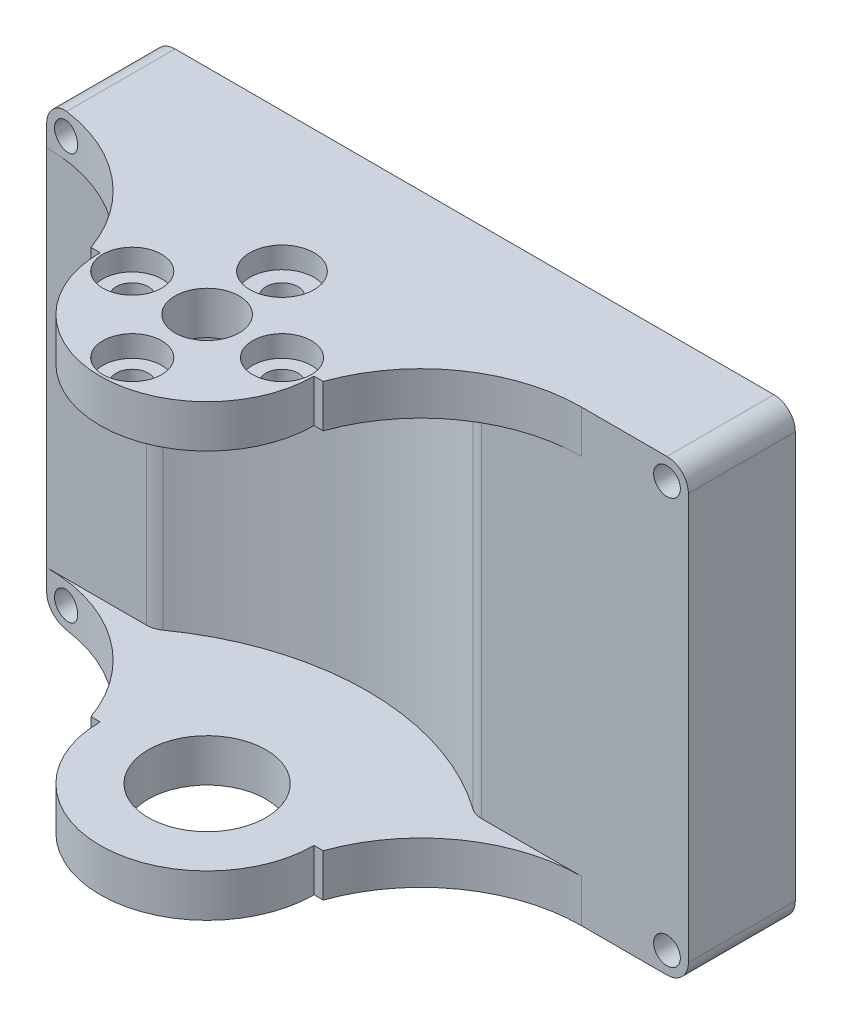
SolidWorks part; units mm, degrees
ref_plane "前视基准面" through (0, 0, 0) normal (0, 0, 1) x (1, 0, 0)
ref_plane "上视基准面" through (0, 0, 0) normal (0, 1, 0) x (1, 0, 0)
ref_plane "右视基准面" through (0, 0, 0) normal (1, 0, 0) x (0, 0, -1)
sketch "草图7" plane through (0, 0, 0) normal (0, 0, 1) x (1, 0, 0)
  line L1 (0, 0) -> (60, 0)
  line L2 (0, 0) -> (0, 42)
  line L3 (0, 42) -> (60, 42)
  line L4 (60, 0) -> (60, 42)
  circle A0 centre (2, 40) radius 1.25
  circle A1 centre (2, 2) radius 1.25
  circle A2 centre (58, 2) radius 1.25
  circle A3 centre (58, 40) radius 1.25
  dimension "D3" = 2.5
  dimension "D4" = 2.5
  dimension "D5" = 2.5
  dimension "D6" = 2.5
  dimension "D7" = 2
  dimension "D10" = 2
  dimension "D12" = 2
  dimension "D13" = 2
  dimension "D14" = 2
  dimension "D1" = 42
  dimension "D2" = 60
  dimension "D8" = 2
  dimension "D9" = 2
  dimension "D11" = 2
extrude "凸台-拉伸4" add sketch "草图7" along normal blind 10
sketch "草图8" plane through (0, 0, 0) normal (0, -1, 0) x (1, 0, 0)
  line L0 (0, 10) -> (0, 0) construction
  line L1 (0, 0) -> (60, 0) construction
  circle A0 centre (25, 30) radius 25
  dimension "D1" = 50
  dimension "D2" = 25
  dimension "D3" = 30
extrude "切除-拉伸2" cut sketch "草图8" against normal blind 50
sketch "草图9" plane through (0, 0, 0) normal (0, -1, 0) x (1, 0, 0)
  line L0 (0, 10) -> (0, 0) construction
  line L1 (0, 0) -> (60, 0) construction
  line L2 (0, 10) -> (0, 20)
  line L3 (50, 20) -> (50, 9.9121)
  line L4 (0, 20) -> (15, 20)
  line L5 (50, 20) -> (35, 20)
  line L6 (50, 9.9121) -> (40, 9.9121)
  circle A0 centre (25, 20) radius 10
  circle A1 centre (25, 20) radius 5.5
  circle A2 centre (25, 20) radius 25
  arc M1 (40, 10) -> (10, 10) centre (25, 30) cw
  line M2 (10, 10) -> (0, 10)
  line M6 (60, 10) -> (40, 10)
  dimension "D2" = 20
  dimension "D3" = 11
  dimension "D4" = 20
  dimension "D5" = 50
  dimension "D1" = 25
extrude "凸台-拉伸5" add sketch "草图9" against normal blind 4 contours A0 A1 | A2 L5 A0 L4 M1 | A2 L2 M2 | A2 L3 M6
sketch "草图10" plane through (0, 0, 0) normal (0, -1, 0) x (1, 0, 0)
  line L0 (14.1421, 20) -> (0, 20)
  line L1 (0, 20) -> (15, 20) construction
  line L2 (0, 0) -> (60, 0) construction
  line L3 (35, 20) -> (35.8579, 20)
  line L4 (35.8579, 20) -> (50, 20)
  line L5 (50, 20) -> (50, 10)
  line L6 (0, 10) -> (0, 20)
  line L7 (0, 20) -> (0, 0) construction
  circle A1 centre (50, 25) radius 15
  circle A2 centre (0, 25) radius 15
  arc A4 (35, 20) -> (15, 20) centre (25, 20) ccw construction
  line M3 (50, 10) -> (50, 20)
  line M4 (50, 20) -> (35, 20)
  line M6 (15, 20) -> (0, 20)
  line M7 (0, 20) -> (0, 0)
  dimension "D1" = 25
  dimension "D2" = 30
  dimension "D4" = 30
  dimension "D6" = 25
  dimension "D5" = 25
  dimension "D3" = 25
extrude "切除-拉伸4" cut sketch "草图10" against normal blind 4 contours A2 M7 M6 | A1 M4 M3
sketch "草图11" plane through (0, 42, 0) normal (0, 1, 0) x (1, 0, 0)
  line L4 (10, -10) -> (0, -10)
  line L5 (14.1421, -20) -> (15, -20)
  line L6 (35, -20) -> (35.8579, -20)
  line L7 (50, -10) -> (40, -10)
  line L8 (10, -10) -> (0, -10)
  line L9 (14.1421, -20) -> (15, -20)
  line L10 (35, -20) -> (35.8579, -20)
  line L11 (50, -10) -> (40, -10)
  circle A0 centre (25, -20) radius 10
  circle A1 centre (25, -13) radius 1.5
  circle A2 centre (25, -27) radius 1.5
  circle A3 centre (32, -20) radius 1.5
  circle A4 centre (18, -20) radius 1.5
  circle A5 centre (25, -20) radius 3
  arc A9 (14.1421, -20) -> (0, -10) centre (0, -25) ccw
  arc A10 (15, -20) -> (35, -20) centre (25, -20) ccw
  arc A11 (50, -10) -> (35.8579, -20) centre (50, -25) ccw
  arc A12 (40, -10) -> (10, -10) centre (25, -30) ccw
  arc A13 (14.1421, -20) -> (0, -10) centre (0, -25) ccw
  arc A14 (15, -20) -> (35, -20) centre (25, -20) ccw
  arc A15 (50, -10) -> (35.8579, -20) centre (50, -25) ccw
  arc A16 (40, -10) -> (10, -10) centre (25, -30) ccw
  line M9 (0, -10) -> (10, -10)
  arc M10 (10, -10) -> (40, -10) centre (25, -30) cw
  line M11 (40, -10) -> (60, -10)
  dimension "D1" = 20
  dimension "D2" = 3
  dimension "D3" = 3
  dimension "D4" = 3
  dimension "D5" = 3
  dimension "D6" = 14
  dimension "D7" = 14
  dimension "D8" = 7
  dimension "D9" = 7
  dimension "D10" = 0
extrude "凸台-拉伸6" add sketch "草图11" against normal blind 4 contours A15 A13 L9 A0 L10 M11 M10 M9 | A0 A4 A3 A2 A1
sketch "草图12" plane through (0, 42, 0) normal (0, 1, 0) x (1, 0, 0)
  circle A0 centre (25, -13) radius 3
  circle A1 centre (18, -20) radius 2.75
  circle A2 centre (25, -27) radius 2.75
  circle A3 centre (32, -20) radius 2.75
  dimension "D1" = 6
  dimension "D2" = 5.5
  dimension "D3" = 5.5
  dimension "D4" = 5.5
extrude "切除-拉伸6" cut sketch "草图12" against normal blind 2
sketch "草图15" plane through (0, 0, 0) normal (0, 0, -1) x (-1, 0, 0)
  circle A0 centre (-2, 2) radius 1.25 construction
  circle A1 centre (-2, 40) radius 1.25 construction
  circle A2 centre (-2, 2) radius 1.25
  circle A3 centre (-2, 40) radius 1.25
extrude "切除-拉伸7" cut sketch "草图15" against normal blind 22
fillet "圆角1" radius 2 1 edges at (0, 0, 5)
fillet "圆角2" radius 2 1 edges at (60, 0, 5)
fillet "圆角3" radius 2 1 edges at (60, 42, 5)
fillet "圆角4" radius 2 1 edges at (0, 42, 5)
fillet "圆角6" radius 2 1 edges at (40, 21, 10)
fillet "圆角7" radius 2 1 edges at (10, 21, 10)
